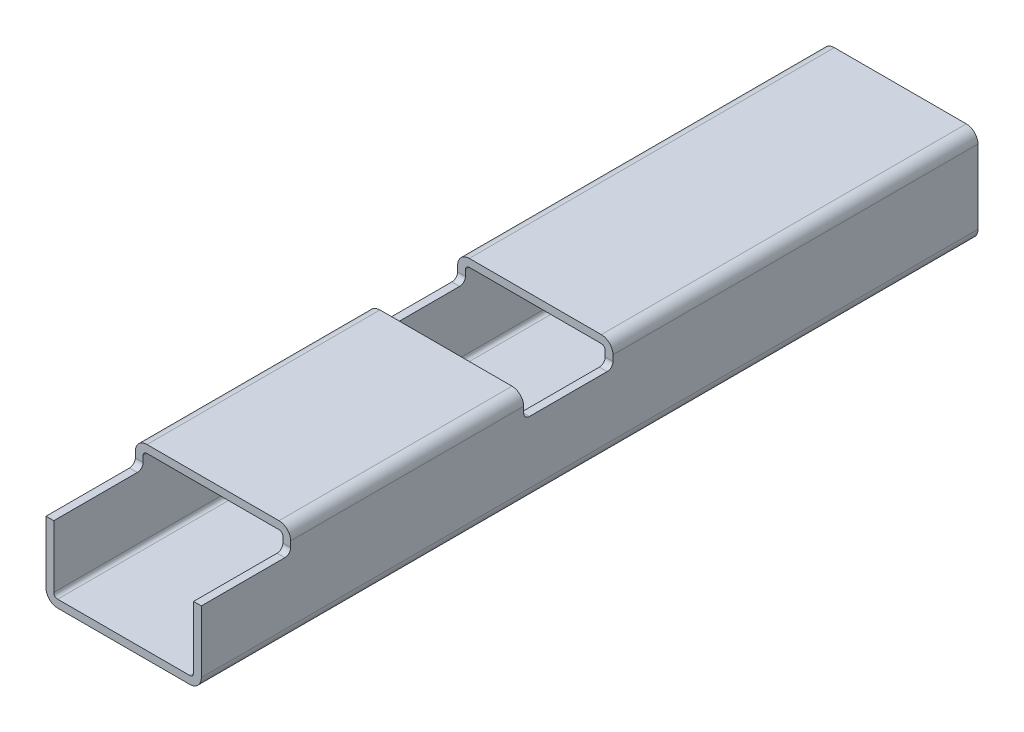
SolidWorks part; units mm, degrees
material "Простая углеродистая сталь"
ref_plane "Front" through (0, 0, 0) normal (0, 0, 1) x (1, 0, 0)
ref_plane "Top" through (0, 0, 0) normal (0, 1, 0) x (1, 0, 0)
ref_plane "Right" through (0, 0, 0) normal (1, 0, 0) x (0, 0, -1)
sketch "Эскиз1" plane through (0, 0, 0) normal (0, 0, 1) x (1, 0, 0)
  line L0 (-34, -21) -> (34, -21)
  line L1 (-34, -25) -> (34, -25)
  line L2 (-40, -19) -> (-40, 19)
  line L3 (-34, 25) -> (34, 25)
  line L4 (40, -19) -> (40, 19)
  line L5 (-40, -25) -> (40, 25) construction
  line L6 (-40, 25) -> (40, -25) construction
  line L7 (36, -19) -> (36, 19)
  line L8 (-34, 21) -> (34, 21)
  line L9 (-36, -19) -> (-36, 19)
  arc A0 (-34, -25) -> (-40, -19) centre (-34, -19) cw
  arc A1 (34, -25) -> (40, -19) centre (34, -19) ccw
  arc A2 (34, 25) -> (40, 19) centre (34, 19) cw
  arc A3 (-40, 19) -> (-34, 25) centre (-34, 19) cw
  arc A4 (34, -21) -> (36, -19) centre (34, -19) ccw
  arc A5 (34, 21) -> (36, 19) centre (34, 19) cw
  arc A6 (-36, 19) -> (-34, 21) centre (-34, 19) cw
  arc A7 (-34, -21) -> (-36, -19) centre (-34, -19) cw
  point P0 (0, 0)
  dimension "D3" = 6
  dimension "D1" = 80
  dimension "D2" = 50
  dimension "D4" = 4
extrude "Бобышка-Вытянуть1" add sketch "Эскиз1" along normal blind 400
sketch "Эскиз2" plane through (40, 0, 0) normal (1, 0, 0) x (0, 0, -1)
  line L0 (-400, -19) -> (-400, 19) construction
  line L1 (-400, 13) -> (-357, 13)
  line L2 (-400, 13) -> (-400, 25)
  line L3 (-400, 25) -> (-354, 25)
  line L4 (-354, 16) -> (-354, 25)
  line L5 (-400, 25) -> (0, 25) construction
  line L6 (-231, 13) -> (-191, 13)
  line L7 (-234, 16) -> (-234, 25)
  line L8 (-234, 25) -> (-188, 25)
  line L9 (-188, 16) -> (-188, 25)
  arc A0 (-231, 13) -> (-234, 16) centre (-231, 16) cw
  arc A1 (-357, 13) -> (-354, 16) centre (-357, 16) ccw
  arc A2 (-191, 13) -> (-188, 16) centre (-191, 16) ccw
  dimension "D4" = 3
  dimension "D1" = 46
  dimension "D2" = 120
  dimension "D3" = 12
extrude "Вырез-Вытянуть1" cut sketch "Эскиз2" against normal through all
